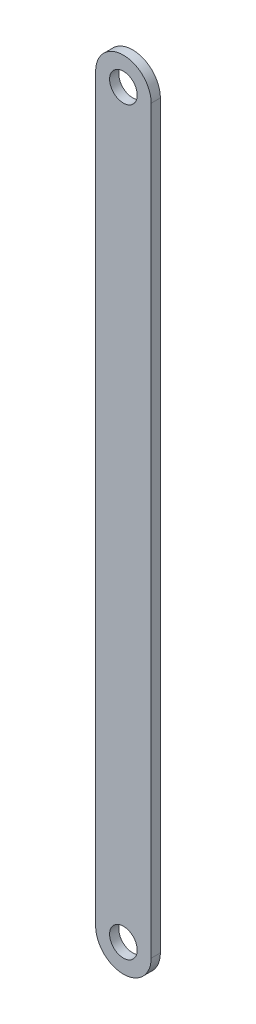
SolidWorks part; units mm, degrees
ref_plane "前视基准面" through (0, 0, 0) normal (0, 0, 1) x (1, 0, 0)
ref_plane "上视基准面" through (0, 0, 0) normal (0, 1, 0) x (1, 0, 0)
ref_plane "右视基准面" through (0, 0, 0) normal (1, 0, 0) x (0, 0, -1)
sketch "草图1" plane through (0, 0, 0) normal (0, 0, 1) x (1, 0, 0)
  line L0 (0, 0) -> (0, -161) construction
  line L1 (6.0386, 0) -> (6.0386, -161)
  line L2 (-6.0386, -161) -> (-6.0386, 0)
  circle A0 centre (0, 0) radius 3
  circle A1 centre (0, -161) radius 3
  arc A2 (6.0386, -161) -> (-6.0386, -161) centre (0, -161) cw
  arc A3 (6.0386, 0) -> (-6.0386, 0) centre (0, 0) ccw
extrude "凸台-拉伸1" add sketch "草图1" along normal blind 2 contours L1 A2 L2 A3
